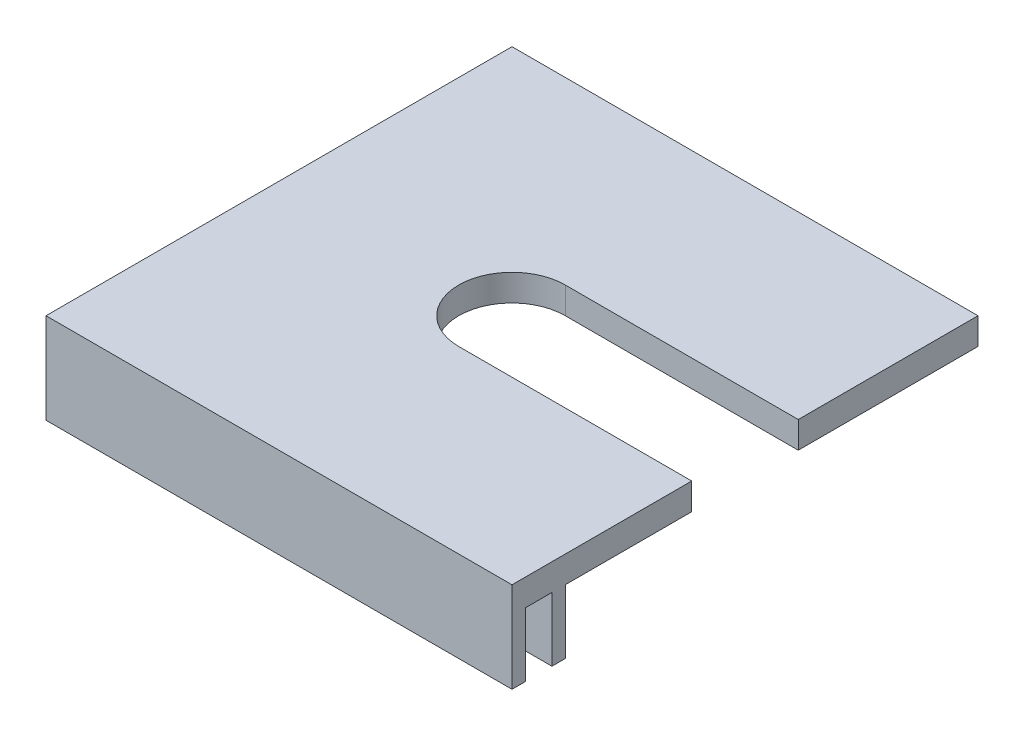
SolidWorks part; units mm, degrees
ref_plane "Front Plane" through (0, 0, 0) normal (0, 0, 1) x (1, 0, 0)
ref_plane "Top Plane" through (0, 0, 0) normal (0, 1, 0) x (1, 0, 0)
ref_plane "Right Plane" through (0, 0, 0) normal (1, 0, 0) x (0, 0, -1)
sketch "Sketch1" plane through (0, 0, 0) normal (0, 1, 0) x (1, 0, 0)
  line L0 (17.5, 13.5) -> (35, 13.5)
  line L1 (0, 0) -> (35, 0)
  line L2 (0, 0) -> (0, 35)
  line L3 (0, 35) -> (35, 35)
  line L4 (35, 0) -> (35, 35)
  line L5 (35, 13.5) -> (35, 21.5)
  line L6 (35, 21.5) -> (17.5, 21.5)
  line L7 (17.5, 35) -> (17.5, 0) construction
  line L8 (0, 17.5) -> (35, 17.5) construction
  circle A1 centre (17.5, 17.5) radius 4
  point P15 (0, 0)
  dimension "D2" = 8
  dimension "D1" = 35
extrude "Boss-Extrude1" add sketch "Sketch1" along normal blind 2 contours A1 L6 L4 L3 L2 L1 L0
sketch "Sketch2" plane through (0, 0, 0) normal (0, -1, 0) x (1, 0, 0)
  line L0 (35, 0) -> (0, 0)
  line L1 (0, 0) -> (0, -35)
  line L2 (0, -35) -> (4, -35)
  line L3 (0, -35) -> (35, -35) construction
  line L4 (4, -35) -> (4, -4)
  line L5 (4, -4) -> (35, -4)
  line L6 (35, 0) -> (35, -13.5) construction
  line L7 (35, 0) -> (35, -4)
  line L10 (35, -2.4387) -> (35, -1)
  line L11 (35, -1) -> (1, -1)
  line L12 (1, -1) -> (1, -35)
  line L13 (1, -35) -> (2.9356, -35)
  line L14 (35, -2) -> (0, -2) construction
  line L15 (2, -35) -> (2, 0) construction
  line L16 (35, -3) -> (1, -3)
  line L17 (3, -1) -> (3, -35)
  point P26 (0, 0)
  point P29 (0, 0)
  line M19 (35, -13.5) -> (35, 0)
  line M20 (35, 0) -> (0, 0)
  line M21 (0, 0) -> (0, -35)
  line M22 (0, -35) -> (35, -35)
  dimension "D1" = 4
  dimension "D2" = 2
  dimension "D3" = 2
extrude "Boss-Extrude2" add sketch "Sketch2" along normal blind 5 contours L16 L17 L2 L4 L5 M19 | L12 L11 M19 M20 M21 M22
chamfer "Chamfer1" distance 0.2 angle 45 12 edges at (0.5, -5, -35) (0, -5, -17.5) (17.5, -5, 0) (35, -5, -0.5) (18, -5, -1) (1, -5, -18) (35, -5, -3.5) (19.5, -5, -4) (4, -5, -19.5) (3.5, -5, -35) (3, -5, -19) (19, -5, -3)
